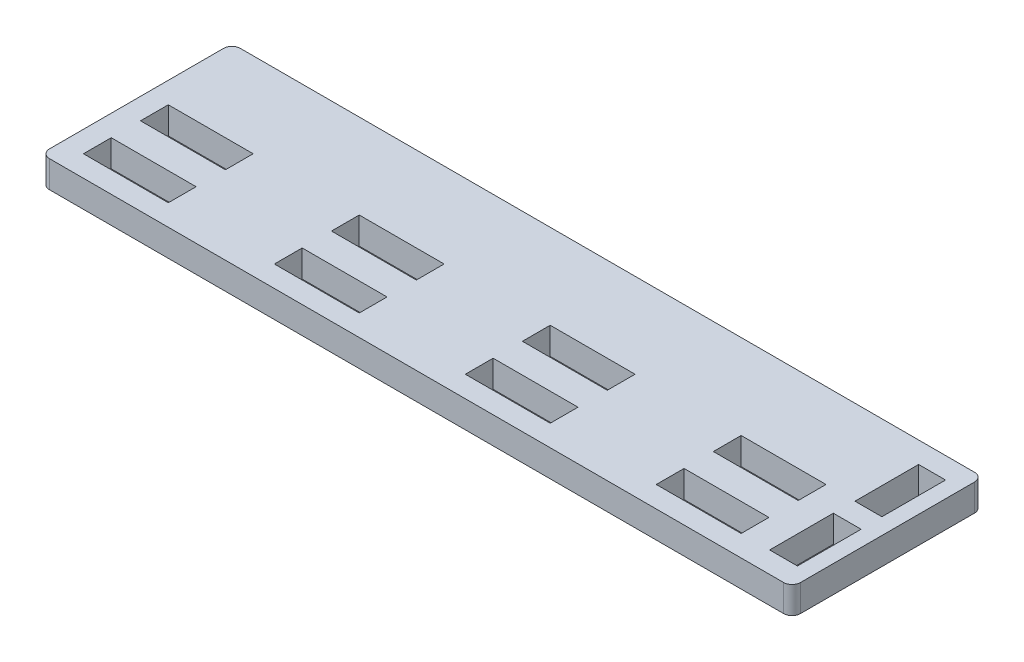
SolidWorks part; units mm, degrees
ref_plane "Front Plane" through (0, 0, 0) normal (0, 0, 1) x (1, 0, 0)
ref_plane "Top Plane" through (0, 0, 0) normal (0, 1, 0) x (1, 0, 0)
ref_plane "Right Plane" through (0, 0, 0) normal (1, 0, 0) x (0, 0, -1)
sketch "Sketch1" plane through (0, 0, 0) normal (0, 1, 0) x (1, 0, 0)
  line L0 (0, 0) -> (0, 20) construction
  line L1 (0, 0) -> (0, -25) construction
  line L2 (0, 0) -> (-170, 0) construction
  line L3 (-170, 0) -> (-170, 20)
  line L4 (-170, 20) -> (0, 20)
  line L6 (0, -25) -> (-170, -25)
  line L7 (-170, -25) -> (-170, 0)
  line L8 (0, 0) -> (7, 0) construction
  line L9 (0, -25) -> (7, -25)
  line L10 (7, -25) -> (7, 20)
  line L11 (7, 20) -> (0, 20)
  dimension "D1" = 20
  dimension "D2" = 25
  dimension "D3" = 170
  dimension "D4" = 7
extrude "Boss-Extrude1" add sketch "Sketch1" along normal blind 6.35
sketch "Sketch2" plane through (0, 6.35, 0) normal (0, 1, 0) x (1, 0, 0)
  line L0 (0, 0) -> (7, 0) construction
  line L1 (7, -25) -> (7, 20) construction
  line L2 (0, 0) -> (0, 20) construction
  line L3 (7, 20) -> (-170, 20) construction
  line L4 (0, 0) -> (-170, 0) construction
  line L5 (-170, 20) -> (-170, -25) construction
  line L6 (0, 0) -> (0, -25) construction
  line L7 (-170, -25) -> (7, -25) construction
  line L8 (-120, -13.45) -> (-100, -13.45)
  line L9 (-165, -13.45) -> (-145, -13.45)
  line L10 (-165, -13.45) -> (-165, -20)
  line L11 (-165, -20) -> (-145, -20)
  line L12 (-145, -13.45) -> (-145, -20)
  line L41 (-120, -13.45) -> (-120, -20)
  line L42 (-120, -20) -> (-100, -20)
  line L43 (-100, -13.45) -> (-100, -20)
  line L44 (-75, -13.45) -> (-55, -13.45)
  line L45 (-75, -13.45) -> (-75, -20)
  line L46 (-75, -20) -> (-55, -20)
  line L47 (-55, -13.45) -> (-55, -20)
  line L48 (-30, -13.45) -> (-10, -13.45)
  line L49 (-30, -13.45) -> (-30, -20)
  line L50 (-30, -20) -> (-10, -20)
  line L51 (-10, -13.45) -> (-10, -20)
  line L60 (-165, -13.45) -> (-120, -13.45) construction
  line L61 (-120, 0) -> (-120, -6.55)
  line L62 (-165, 0) -> (-145, 0)
  line L63 (-165, 0) -> (-165, -6.55)
  line L64 (-165, -6.55) -> (-145, -6.55)
  line L65 (-145, 0) -> (-145, -6.55)
  line L66 (-120, 0) -> (-100, 0)
  line L67 (-100, 0) -> (-100, -6.55)
  line L68 (-120, -6.55) -> (-100, -6.55)
  line L69 (-75, 0) -> (-75, -6.55)
  line L70 (-75, 0) -> (-55, 0)
  line L71 (-55, 0) -> (-55, -6.55)
  line L72 (-75, -6.55) -> (-55, -6.55)
  line L73 (-30, 0) -> (-30, -6.55)
  line L74 (-30, 0) -> (-10, 0)
  line L75 (-10, 0) -> (-10, -6.55)
  line L76 (-30, -6.55) -> (-10, -6.55)
  line L77 (-165, 0) -> (-120, 0) construction
  dimension "D1" = 4
  dimension "D2" = 45
  dimension "D3" = 20
  dimension "D4" = 6.55
  dimension "D5" = 5
  dimension "D6" = 5
  dimension "D7" = 20
  dimension "D8" = 6.55
  dimension "D9" = 5
  dimension "D11" = 45
  dimension "D10" = 4
extrude "Cut-Extrude1" cut sketch "Sketch2" against normal through all contours L63 L62 L65 L64 | L10 L9 L12 L11 | L61 L68 L67 L66 | L8 L43 L42 L41 | L69 L72 L71 L70 | L44 L47 L46 L45 | L48 L51 L50 L49 | L73 L76 L75 L74
sketch "Sketch4" plane through (0, 6.35, 0) normal (0, 1, 0) x (1, 0, 0)
  line L0 (0, 0) -> (7, 0) construction
  line L1 (7, -25) -> (7, 20) construction
  line L2 (0, 0) -> (0, -25) construction
  line L3 (-170, -25) -> (7, -25) construction
  line L4 (0, 0) -> (0, 20) construction
  line L5 (7, 20) -> (-170, 20) construction
  line L6 (0, 0) -> (-170, 0) construction
  line L7 (-170, 20) -> (-170, -25) construction
  line L9 (3.275, -20) -> (-3.275, -20)
  line L10 (3.275, -20) -> (3.275, -5)
  line L11 (3.275, -5) -> (-3.275, -5)
  line L12 (-3.275, -20) -> (-3.275, -5)
  line L13 (-3.175, 15) -> (3.175, 15)
  line L14 (-3.175, 15) -> (-3.175, 0)
  line L15 (-3.175, 0) -> (3.175, 0)
  line L16 (3.175, 15) -> (3.175, 0)
  point P18 (0, -20)
  point P23 (0, 0)
  dimension "D1" = 6.55
  dimension "D2" = 15
  dimension "D3" = 5
  dimension "D4" = 6.35
  dimension "D5" = 15
  dimension "D6" = 5
extrude "Cut-Extrude2" cut sketch "Sketch4" against normal through all
fillet "Fillet1" radius 2 4 edges at (7, 3.175, -20) (7, 3.175, 25) (-170, 3.175, 25) (-170, 3.175, -20)
